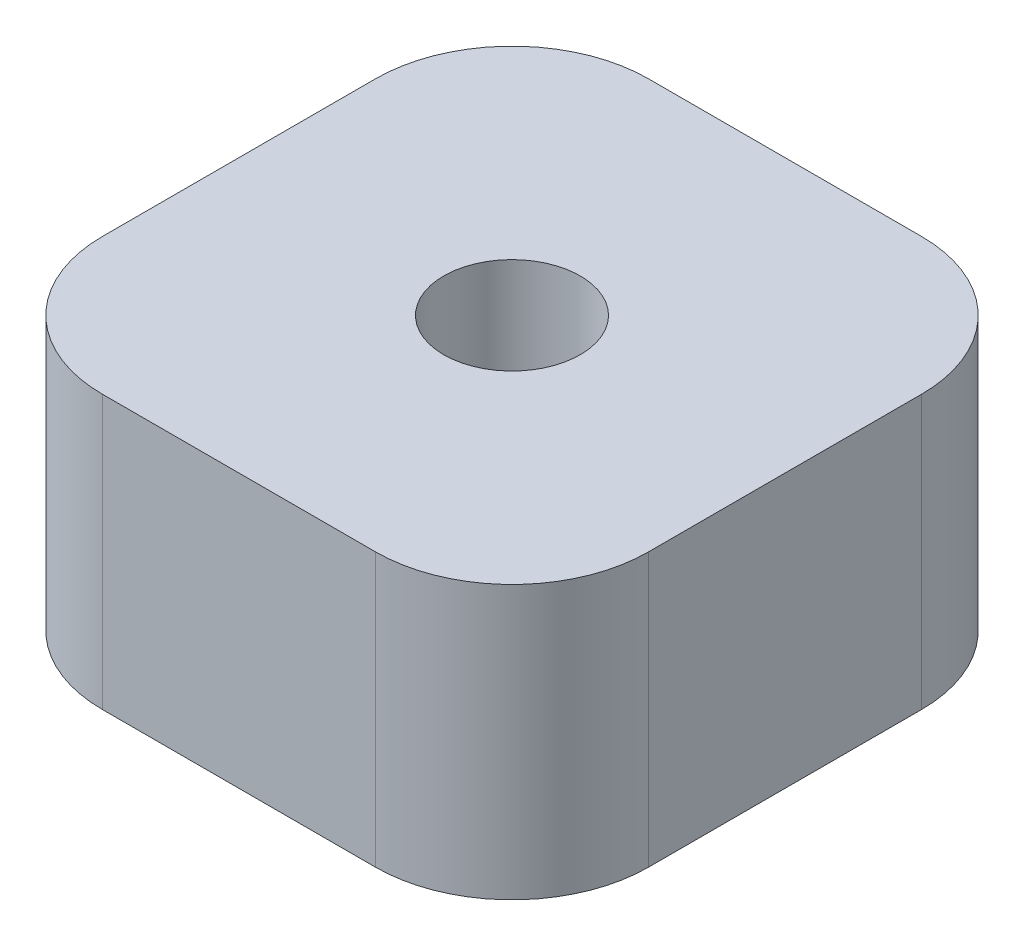
SolidWorks part; units mm, degrees
ref_plane "Front Plane" through (0, 0, 0) normal (0, 0, 1) x (1, 0, 0)
ref_plane "Top Plane" through (0, 0, 0) normal (0, 1, 0) x (1, 0, 0)
ref_plane "Right Plane" through (0, 0, 0) normal (1, 0, 0) x (0, 0, -1)
sketch "Sketch1" plane through (0, 0, 0) normal (0, 1, 0) x (1, 0, 0)
  line L1 (-12.7, -12.7) -> (12.7, -12.7)
  line L2 (-12.7, -12.7) -> (-12.7, 12.7)
  line L3 (-12.7, 12.7) -> (12.7, 12.7)
  line L4 (12.7, -12.7) -> (12.7, 12.7)
  line L5 (0, 12.7) -> (0, -12.7) construction
  line L6 (-12.7, 0) -> (12.7, 0) construction
  circle A0 centre (0, 0) radius 3.175
  point P0 (0, 0)
  dimension "D3" = 6.35
  dimension "D1" = 25.4
  dimension "D2" = 25.4
extrude "Boss-Extrude1" add sketch "Sketch1" along normal blind 12.7
fillet "Fillet1" radius 6.35 4 edges at (12.7, 6.35, 12.7) (12.7, 6.35, -12.7) (-12.7, 6.35, -12.7) (-12.7, 6.35, 12.7)
